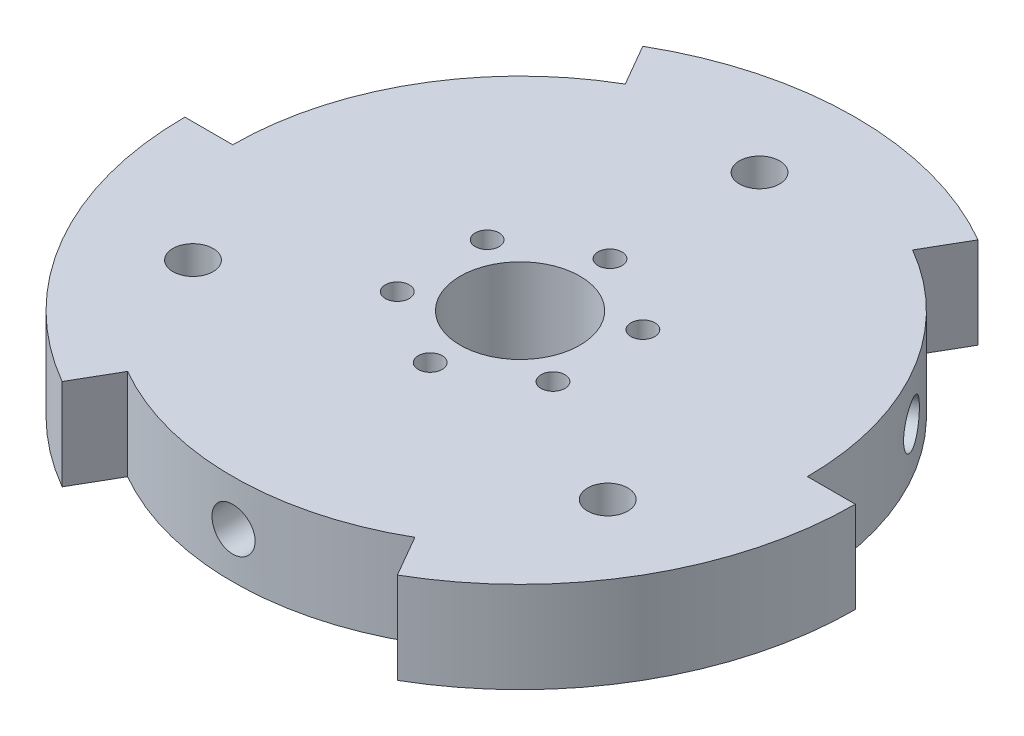
SolidWorks part; units mm, degrees
ref_plane "Front Plane" through (0, 0, 0) normal (0, 0, 1) x (1, 0, 0)
ref_plane "Top Plane" through (0, 0, 0) normal (0, 1, 0) x (1, 0, 0)
ref_plane "Right Plane" through (0, 0, 0) normal (1, 0, 0) x (0, 0, -1)
sketch "Baseplate Sketch" plane through (0, 0, 0) normal (0, 1, 0) x (1, 0, 0)
  line L0 (0, 0) -> (0, 61.4504) construction
  line L1 (-17.5, 30.3109) -> (-15, 25.9808)
  line L2 (17.5, 30.3109) -> (15, 25.9808)
  line L3 (-17.5, 30.3109) -> (-21.8301, 27.8109) construction
  line L4 (17.5, 30.3109) -> (13.1699, 32.8109) construction
  line L5 (17.5, -30.3109) -> (15, -25.9808)
  line L6 (35, 0) -> (30, 0)
  line L7 (-35, 0) -> (-30, 0)
  line L8 (-17.5, -30.3109) -> (-15, -25.9808)
  circle A0 centre (0, 0) radius 30
  circle A1 centre (0, 0) radius 6.25
  arc A2 (-17.5, 30.3109) -> (17.5, 30.3109) centre (0, 0) cw
  arc A3 (35, 0) -> (17.5, -30.3109) centre (0, 0) cw
  arc A4 (-17.5, -30.3109) -> (-35, 0) centre (0, 0) cw
  circle A5 centre (0, 25) radius 2.1
  circle A6 centre (21.6506, -12.5) radius 2.1
  circle A7 centre (-21.6506, -12.5) radius 2.1
  point P15 (0, 35)
  point P25 (0, 0)
  point P31 (0, 0)
  dimension "D1" = 60
  dimension "D2" = 12.5
  dimension "D3" = 35
  dimension "D4" = 90
  dimension "D5" = 5
  dimension "D12" = 4.2
  dimension "D6" = 5
  dimension "D7" = 90
  dimension "D8" = 60
  dimension "D9" = 5
  dimension "D10" = 5
  dimension "D14" = 25
  dimension "D11" = 3
  dimension "D13" = 3
extrude "Boss-Extrude1" add sketch "Baseplate Sketch" along normal blind 9.525 contours A4 L8 A0 L7 | A3 L6 A0 L5 | A2 L1 A0 L2 | A1 | A6 | A7 | A5
ref_plane "Plane1" through (0, 0, 40) normal (0, 0, 1) x (1, 0, 0)
sketch "Sketch2" plane through (0, 0, 40) normal (0, 0, 1) x (1, 0, 0)
  line L0 (0, 9.525) -> (0, 0) construction
  line L4 (15, 9.525) -> (-15, 9.525)
  line L5 (-15, 9.525) -> (-15, 0)
  line L6 (-15, 0) -> (15, 0)
  line L7 (15, 0) -> (15, 9.525)
  line L8 (15, 9.525) -> (-15, 9.525) construction
  line L9 (-15, 9.525) -> (-15, 0) construction
  line L10 (-15, 0) -> (15, 0) construction
  line L11 (15, 0) -> (15, 9.525) construction
  circle A0 centre (0, 4.7625) radius 2.25
  dimension "D1" = 0
  dimension "D2" = 4.5
extrude "Cut-Extrude1" cut sketch "Sketch2" against normal blind 25
pattern_circular "CirPattern1" count 3 over 360 about axis through (0, 0, 0) along (0, 1, 0) of "Cut-Extrude1"
sketch "Sketch3" plane through (0, 9.525, 0) normal (0, 1, 0) x (1, 0, 0)
  circle A2 centre (-8.1276, -4.6925) radius 1.25
  circle A5 centre (0, -9.385) radius 1.25
  circle A6 centre (-8.1276, 4.6925) radius 1.25
  circle A7 centre (0, 9.385) radius 1.25
  circle A8 centre (8.1276, 4.6925) radius 1.25
  circle A9 centre (8.1276, -4.6925) radius 1.25
  point P14 (0, 0)
  dimension "D1" = 2.5
  dimension "D2" = 9.385
  dimension "D3" = 9.385
extrude "Cut-Extrude2" cut sketch "Sketch3" against normal up to surface (9.525 mm away)
